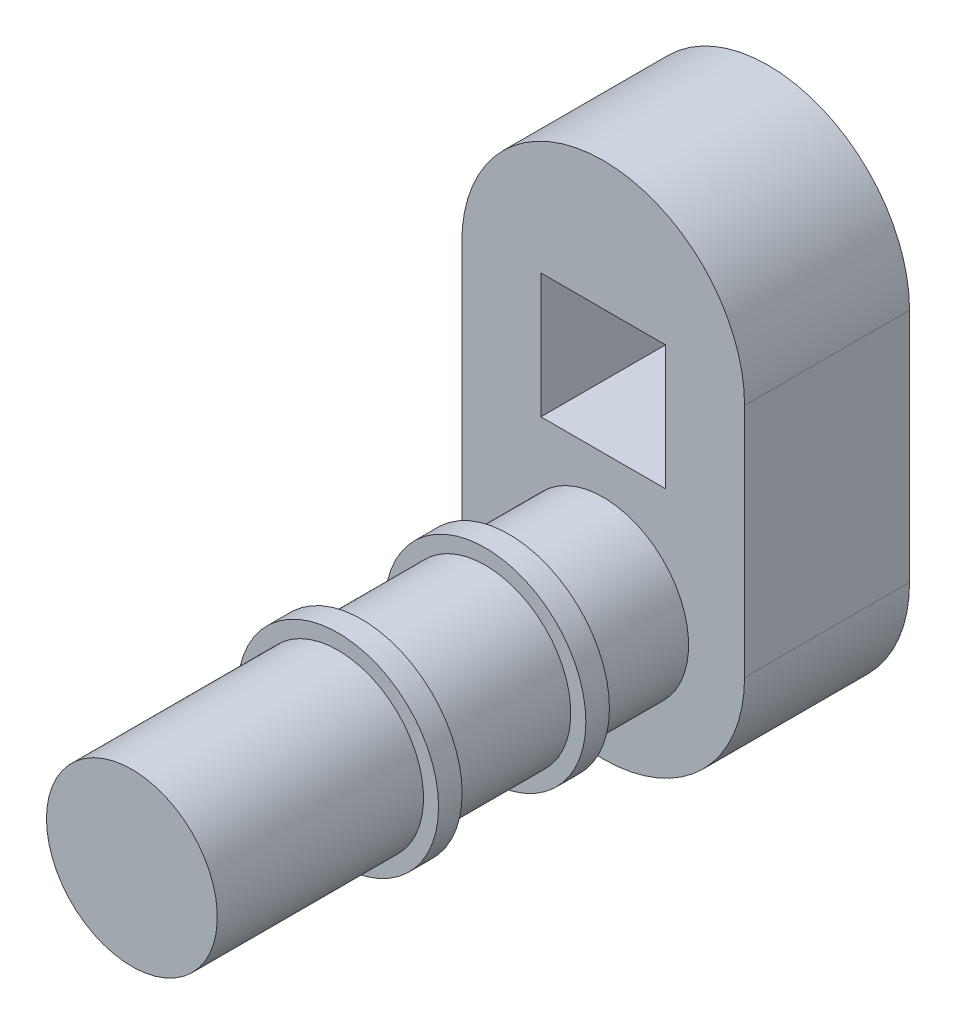
SolidWorks part; units mm, degrees
ref_plane "Front Plane" through (0, 0, 0) normal (0, 0, 1) x (1, 0, 0)
ref_plane "Top Plane" through (0, 0, 0) normal (0, 1, 0) x (1, 0, 0)
ref_plane "Right Plane" through (0, 0, 0) normal (1, 0, 0) x (0, 0, -1)
sketch "Sketch1" plane through (0, 0, 0) normal (0, 0, 1) x (1, 0, 0)
  line L0 (0, 0) -> (0, -10) construction
  line L1 (6, 0) -> (6, -10)
  line L2 (-6, 0) -> (-6, -10)
  line L4 (-2.644, -4.744) -> (2.644, -4.744)
  line L5 (-2.644, -4.744) -> (-2.644, 0.544)
  line L6 (-2.644, 0.544) -> (2.644, 0.544)
  line L7 (2.644, -4.744) -> (2.644, 0.544)
  line L8 (-2.644, -4.744) -> (2.644, 0.544) construction
  line L9 (-2.644, 0.544) -> (2.644, -4.744) construction
  arc A0 (6, 0) -> (-6, 0) centre (0, 0) ccw
  arc A1 (-6, -10) -> (6, -10) centre (0, -10) ccw
  point P3 (0, -5)
  point P8 (0, -2.1)
  dimension "D2" = 6
  dimension "D1" = 10
  dimension "D3" = 7.9
  dimension "D4" = 5.288
extrude "Boss-Extrude1" add sketch "Sketch1" along normal blind 7
sketch "Sketch3" plane through (0, 0, 7) normal (0, 0, 1) x (1, 0, 0)
  line L0 (6, -10) -> (-6, -10) construction
sketch "Sketch4" plane through (0, 0, 0) normal (1, 0, 0) x (0, 0, -1)
  line L0 (-7, -10) -> (-27, -10) construction
  line L1 (-7, -13.625) -> (-11, -13.625)
  line L2 (-27, -13.625) -> (-27, -10)
  line L3 (-18.25, -13.625) -> (-18.25, -14.2645)
  line L4 (-18.25, -14.2645) -> (-17.25, -14.2645)
  line L5 (-17.25, -14.2645) -> (-17.25, -13.625)
  line L6 (-12, -13.625) -> (-12, -14.2645)
  line L7 (-12, -14.2645) -> (-11, -14.2645)
  line L8 (-11, -14.2645) -> (-11, -13.625)
  line L9 (-12, -13.625) -> (-17.25, -13.625)
  line L10 (-18.25, -13.625) -> (-27, -13.625)
  line L11 (-27, -10) -> (-7, -10)
  line L13 (-7, -13.625) -> (-7, -10)
  dimension "D1" = 20
  dimension "D2" = 5.25
  dimension "D3" = 5
  dimension "D4" = 1
  dimension "D5" = 3.625
revolve "Revolve1" add sketch "Sketch4" angle 360 about L0
fillet "Fillet1" radius 1 4 edges at (2.644, -2.1, 0) (0, -4.744, 0) (-2.644, -2.1, 0) (0, 0.544, 0)
